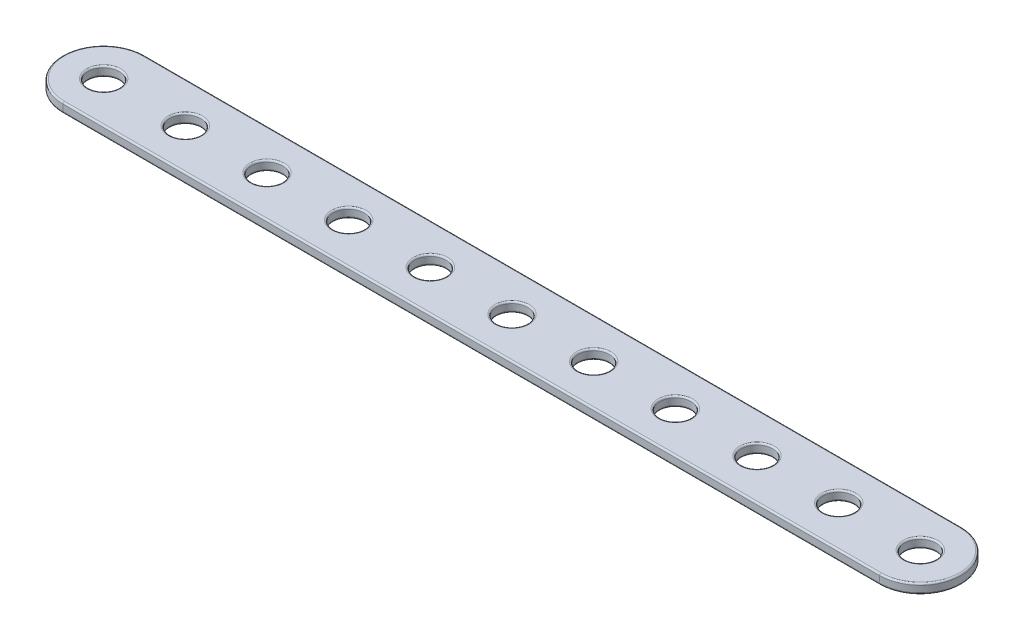
SolidWorks part; units mm, degrees
material "AISI 304"
ref_plane "Front" through (0, 0, 0) normal (0, 0, 1) x (1, 0, 0)
ref_plane "Top" through (0, 0, 0) normal (0, 1, 0) x (1, 0, 0)
ref_plane "Right" through (0, 0, 0) normal (1, 0, 0) x (0, 0, -1)
sketch "Sketch1" plane through (0, 0, 0) normal (0, 1, 0) x (1, 0, 0)
  line L1 (0, 0) -> (127, 0)
  line L3 (0, 12.7) -> (127, 12.7)
  arc A0 (0, 12.7) -> (0, 0) centre (0, 6.35) ccw
  arc A1 (127, 0) -> (127, 12.7) centre (127, 6.35) ccw
  dimension "D1" = 12.7
  dimension "D2" = 127
extrude "Extrude1" add sketch "Sketch1" along normal blind 1.524
sketch "Sketch2" plane through (0, 1.524, 0) normal (0, 1, 0) x (-1, 0, 0)
  line L0 (-127, -12.7) -> (0, -12.7) construction
  circle A0 centre (0, -6.35) radius 2.413
  dimension "D2" = 4.826
  dimension "D1" = 6.35
extrude "Cut-Extrude1" cut sketch "Sketch2" against normal through all
pattern_linear "LPattern1" count 11 spacing 12.7 along (1, 0, 0) of "Cut-Extrude1"
fillet "Fillet1" radius 0.254 30 edges at (63.5, 0, 0) (133.35, 0, -6.35) (63.5, 0, -12.7) (-6.35, 0, -6.35) (0, 0, -3.937) (12.7, 0, -3.937) (25.4, 0, -3.937) (38.1, 0, -3.937) (50.8, 0, -3.937) (63.5, 0, -3.937) (76.2, 0, -3.937) (88.9, 0, -3.937) (101.6, 0, -3.937) (114.3, 0, -3.937) (127, 0, -3.937) (63.5, 1.524, -12.7) (133.35, 1.524, -6.35) (63.5, 1.524, 0) (-6.35, 1.524, -6.35) (0, 1.524, -3.937) (12.7, 1.524, -3.937) (25.4, 1.524, -3.937) (38.1, 1.524, -3.937) (50.8, 1.524, -3.937) (63.5, 1.524, -3.937) (76.2, 1.524, -3.937) (88.9, 1.524, -3.937) (101.6, 1.524, -3.937) (114.3, 1.524, -3.937) (127, 1.524, -3.937)
equation "\"D2@Sketch1\" = \"D3@LPattern1\" *  ( \"D1@LPattern1\" - 1 ) "
